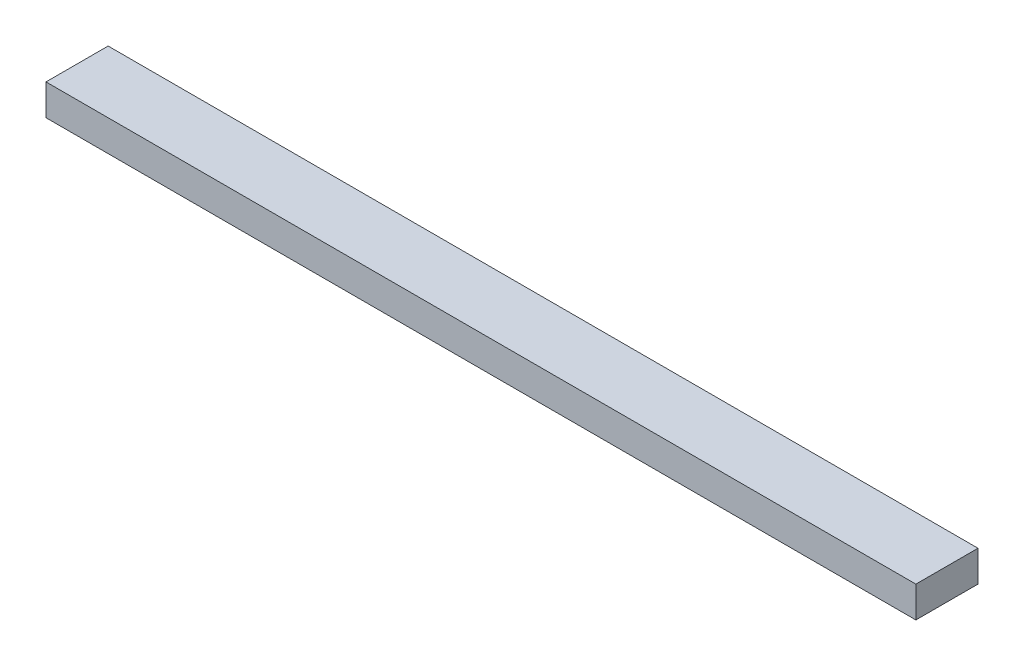
SolidWorks part; units mm, degrees
ref_plane "Plan de face" through (0, 0, 0) normal (0, 0, 1) x (1, 0, 0)
ref_plane "Plan de dessus" through (0, 0, 0) normal (0, 1, 0) x (1, 0, 0)
ref_plane "Plan de droite" through (0, 0, 0) normal (1, 0, 0) x (0, 0, -1)
sketch "Esquisse1" plane through (0, 0, 0) normal (0, 0, 1) x (1, 0, 0)
  line L1 (-101.9982, 26.3575) -> (178.0018, 26.3575)
  line L2 (-101.9982, 26.3575) -> (-101.9982, 16.3575)
  line L3 (-101.9982, 16.3575) -> (178.0018, 16.3575)
  line L4 (178.0018, 26.3575) -> (178.0018, 16.3575)
  dimension "D1" = 280
  dimension "D2" = 10
extrude "Boss.-Extru.1" add sketch "Esquisse1" along normal blind 20
